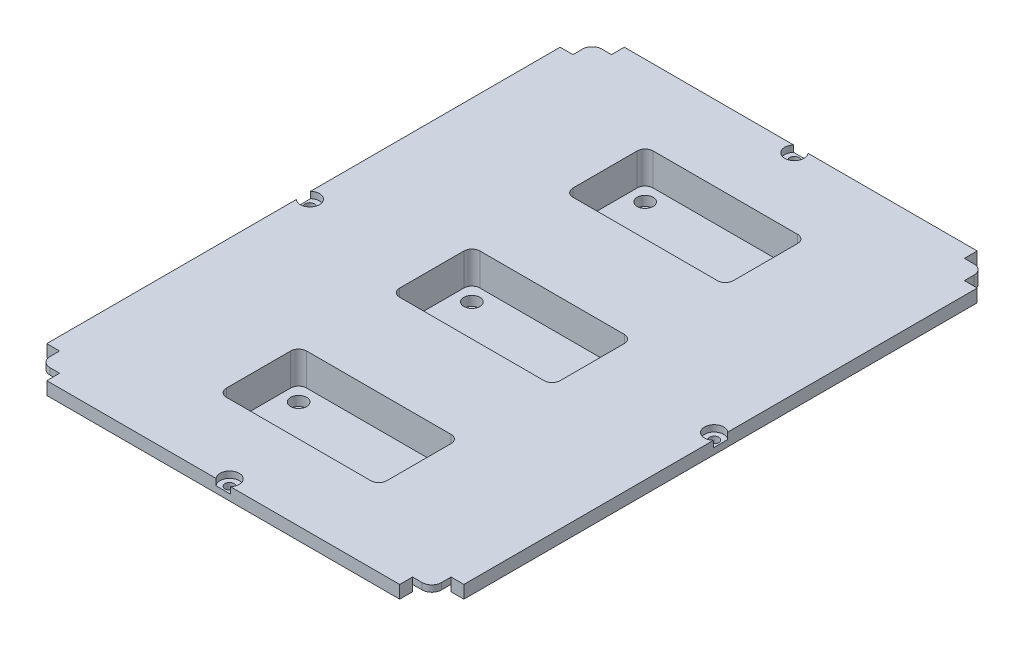
SolidWorks part; units mm, degrees
ref_plane "Спереди" through (0, 0, 0) normal (0, 0, 1) x (1, 0, 0)
ref_plane "Сверху" through (0, 0, 0) normal (0, 1, 0) x (1, 0, 0)
ref_plane "Справа" through (0, 0, 0) normal (1, 0, 0) x (0, 0, -1)
sketch "Эскиз1" plane through (0, 0, 0) normal (0, 1, 0) x (1, 0, 0)
  line L1 (-65, -90) -> (65, -90)
  line L2 (-65, -90) -> (-65, 90)
  line L3 (-65, 90) -> (65, 90)
  line L4 (65, -90) -> (65, 90)
  line L5 (-65, -90) -> (65, 90) construction
  line L6 (-65, 90) -> (65, -90) construction
  point P0 (0, 0)
  dimension "D1" = 130
  dimension "D2" = 180
extrude "Бобышка-Вытянуть1" add sketch "Эскиз1" along normal blind 55
sketch "Эскиз2" plane through (0, 0, 90) normal (0, 0, 1) x (1, 0, 0)
  line L0 (-1050, 27.5) -> (48950, 27.5) construction
  line L1 (-65, 55) -> (-65, 0) construction
  line L2 (0, -999.2777) -> (0, 49000.7223) construction
  line L4 (-22.5, 15) -> (22.5, 15)
  line L5 (-25, 17.5) -> (-25, 37.5)
  line L6 (-22.5, 40) -> (22.5, 40)
  line L7 (25, 17.5) -> (25, 37.5)
  line L8 (-25, 15) -> (25, 40) construction
  line L9 (-25, 40) -> (25, 15) construction
  arc A0 (-22.5, 40) -> (-25, 37.5) centre (-22.5, 37.5) ccw
  arc A1 (-25, 17.5) -> (-22.5, 15) centre (-22.5, 17.5) ccw
  arc A2 (25, 17.5) -> (22.5, 15) centre (22.5, 17.5) cw
  arc A3 (25, 37.5) -> (22.5, 40) centre (22.5, 37.5) ccw
  point P5 (-65, 27.5)
  point P6 (0, 27.5)
  dimension "D3" = 2.5
  dimension "D4" = 2.5
  dimension "D1" = 25
  dimension "D2" = 50
extrude "Вырез-Вытянуть1" cut sketch "Эскиз2" against normal blind 10
sketch "Эскиз4" plane through (0, 55, 0) normal (0, 1, 0) x (1, 0, 0)
  line L0 (0, -1000) -> (0, 49000) construction
  line L1 (-1000, 0) -> (49000, 0) construction
  line L2 (-22.5, 41.5) -> (22.5, 41.5)
  line L3 (-25, 44) -> (-25, 64)
  line L4 (-22.5, 66.5) -> (22.5, 66.5)
  line L5 (-22.5, -12.5) -> (22.5, -12.5)
  line L6 (-25, -10) -> (-25, 10)
  line L7 (-22.5, 12.5) -> (22.5, 12.5)
  line L8 (25, -10) -> (25, 10)
  line L9 (-25, -12.5) -> (25, 12.5) construction
  line L10 (-25, 12.5) -> (25, -12.5) construction
  line L11 (25, 44) -> (25, 64)
  line L12 (-25, 41.5) -> (25, 66.5) construction
  line L13 (-25, 66.5) -> (25, 41.5) construction
  line L14 (-25, -12.5) -> (25, -12.5) [skipped]
  line L15 (-25, -12.5) -> (-25, 12.5) [skipped]
  line L16 (-25, 12.5) -> (25, 12.5) [skipped]
  line L17 (25, -12.5) -> (25, 12.5) [skipped]
  line L18 (-25, -12.5) -> (25, 12.5) construction
  line L19 (-25, 12.5) -> (25, -12.5) construction
  line L20 (-22.5, -66.5) -> (22.5, -66.5)
  line L21 (-25, -64) -> (-25, -44)
  line L22 (-22.5, -41.5) -> (22.5, -41.5)
  line L23 (25, -64) -> (25, -44)
  line L24 (-25, -66.5) -> (25, -41.5) construction
  line L25 (-25, -41.5) -> (25, -66.5) construction
  arc A0 (22.5, -41.5) -> (25, -44) centre (22.5, -44) cw
  arc A1 (25, -64) -> (22.5, -66.5) centre (22.5, -64) cw
  arc A2 (-22.5, -66.5) -> (-25, -64) centre (-22.5, -64) cw
  arc A3 (-25, -44) -> (-22.5, -41.5) centre (-22.5, -44) cw
  arc A4 (-25, 64) -> (-22.5, 66.5) centre (-22.5, 64) cw
  arc A5 (-22.5, 12.5) -> (-25, 10) centre (-22.5, 10) ccw
  arc A6 (25, -10) -> (22.5, -12.5) centre (22.5, -10) cw
  arc A7 (22.5, 66.5) -> (25, 64) centre (22.5, 64) cw
  arc A8 (25, 44) -> (22.5, 41.5) centre (22.5, 44) cw
  arc A9 (-22.5, 41.5) -> (-25, 44) centre (-22.5, 44) cw
  arc A10 (22.5, 12.5) -> (25, 10) centre (22.5, 10) cw
  arc A11 (-22.5, -12.5) -> (-25, -10) centre (-22.5, -10) cw
  point P8 (0, 0)
  point P9 (0, 54)
  point P18 (0, 0)
  point P23 (0, -54)
  dimension "D7" = 2.5
  dimension "D8" = 2.5
  dimension "D1" = 25
  dimension "D2" = 50
  dimension "D5" = 41.5
  dimension "D6" = 41.5
  dimension "D3" = 2
  dimension "D4" = 2
extrude "Вырез-Вытянуть2" cut sketch "Эскиз4" against normal blind 10
mirror "Зеркальное отражение1" about plane through (0, 0, 0) normal (0, 0, 1) of "Вырез-Вытянуть1"
shell "Оболочка1" thickness 4
sketch "Эскиз5" plane through (-65, 0, 0) normal (-1, 0, 0) x (0, 0, 1)
  line L0 (45, 28.75) -> (45, 11.25) construction
  line L2 (90, 55) -> (90, 0) construction
  line L4 (-90, 0) -> (90, 0) construction
  line L7 (-1075, 20) -> (48925, 20) construction
  line L8 (-90, 55) -> (-90, 0) construction
  circle A3 centre (45, 28.75) radius 1.45
  circle A4 centre (45, 11.25) radius 1.45
  circle A5 centre (65.6, 20) radius 4
  circle A6 centre (-65.6, 20) radius 5
  dimension "D2" = 17.5
  dimension "D3" = 20
  dimension "D6" = 10
  dimension "D1" = 17.5
  dimension "D5" = 2.9
  dimension "D9" = 45
  dimension "D10" = 20.6
  dimension "D11" = 8
  dimension "D4" = 24.4
extrude "Вырез-Вытянуть3" cut sketch "Эскиз5" against normal blind 15
sketch "Эскиз6" plane through (-65, 0, 0) normal (-1, 0, 0) x (0, 0, 1)
  circle A2 centre (45, 28.75) radius 3
  circle A3 centre (45, 11.25) radius 3
  dimension "D1" = 6
extrude "Вырез-Вытянуть4" cut sketch "Эскиз6" against normal blind 2.5
sketch "Эскиз11" plane through (-61, 0, 0) normal (1, 0, 0) x (0, 0, -1)
  circle A1 centre (-65.6, 20) radius 5
  dimension "D1" = 10
extrude "Вырез-Вытянуть16" cut sketch "Эскиз11" against normal blind 1
mirror "Зеркальное отражение2" about plane through (0, 0, 0) normal (1, 0, 0) of "Вырез-Вытянуть3", "Вырез-Вытянуть4", "Вырез-Вытянуть16"
sketch "Эскиз12" plane through (0, 11, 0) normal (0, -1, 0) x (-1, 0, 0)
  line L0 (-1014.7864, -78) -> (48985.2136, -78) construction
  line L1 (22.5, -76) -> (-22.5, -76) construction
  line L2 (0, -1061) -> (0, 48939) construction
  line L3 (-10, -1061) -> (-10, 48939) construction
  line L4 (10, -1061) -> (10, 48939) construction
  circle A0 centre (-10, -78) radius 1.45
  circle A1 centre (10, -78) radius 1.45
  point P7 (0, -76)
  dimension "D4" = 2.9
  dimension "D1" = 2
  dimension "D2" = 20
  dimension "D3" = 10
extrude "Вырез-Вытянуть17" cut sketch "Эскиз12" against normal blind 14
sketch "Эскиз15" plane through (0, 45, 0) normal (0, 1, 0) x (1, 0, 0)
  line L0 (-1010.1672, -62.5) -> (48989.8328, -62.5) construction
  line L1 (0, -1031.5) -> (0, 48968.5) construction
  line L2 (-7.6, -63.8) -> (7.6, -63.8)
  line L3 (-7.6, -63.8) -> (-7.6, -61.2)
  line L4 (-7.6, -61.2) -> (7.6, -61.2)
  line L5 (7.6, -63.8) -> (7.6, -61.2)
  line L6 (-7.6, -63.8) -> (7.6, -61.2) construction
  line L7 (-7.6, -61.2) -> (7.6, -63.8) construction
  line L8 (22.5, -41.5) -> (-22.5, -41.5) construction
  line L9 (-22.5, -66.5) -> (22.5, -66.5) construction
  line L10 (-7.6, -9.8) -> (7.6, -9.8)
  line L11 (-7.6, -9.8) -> (-7.6, -7.2)
  line L12 (-7.6, -7.2) -> (7.6, -7.2)
  line L13 (7.6, -9.8) -> (7.6, -7.2)
  line L14 (-7.6, -9.8) -> (7.6, -7.2) construction
  line L15 (-7.6, -7.2) -> (7.6, -9.8) construction
  line L16 (-7.6, 44.2) -> (7.6, 44.2)
  line L17 (-7.6, 44.2) -> (-7.6, 46.8)
  line L18 (-7.6, 46.8) -> (7.6, 46.8)
  line L19 (7.6, 44.2) -> (7.6, 46.8)
  line L20 (-7.6, 44.2) -> (7.6, 46.8) construction
  line L21 (-7.6, 46.8) -> (7.6, 44.2) construction
  line L23 (22.5, 12.5) -> (-22.5, 12.5) construction
  line L24 (-7.6, -59.8) -> (7.6, -59.8)
  line L25 (-7.6, -59.8) -> (-7.6, -57.2)
  line L26 (-7.6, -57.2) -> (7.6, -57.2)
  line L27 (7.6, -59.8) -> (7.6, -57.2)
  line L28 (-7.6, -59.8) -> (7.6, -57.2) construction
  line L29 (-7.6, -57.2) -> (7.6, -59.8) construction
  line L30 (-7.6, -5.8) -> (7.6, -5.8)
  line L31 (-7.6, -5.8) -> (-7.6, -3.2)
  line L32 (-7.6, -3.2) -> (7.6, -3.2)
  line L33 (7.6, -5.8) -> (7.6, -3.2)
  line L34 (-7.6, -5.8) -> (7.6, -3.2) construction
  line L35 (-7.6, -3.2) -> (7.6, -5.8) construction
  line L36 (-7.6, 48.2) -> (7.6, 48.2)
  line L37 (-7.6, 48.2) -> (-7.6, 50.8)
  line L38 (-7.6, 50.8) -> (7.6, 50.8)
  line L39 (7.6, 48.2) -> (7.6, 50.8)
  line L40 (-7.6, 48.2) -> (7.6, 50.8) construction
  line L41 (-7.6, 50.8) -> (7.6, 48.2) construction
  line L42 (-22.5, -12.5) -> (22.5, -12.5) construction
  circle A0 centre (-20, -46.5) radius 2.5
  circle A1 centre (20, -46.5) radius 2.5
  circle A2 centre (-20, 7.5) radius 2.5
  circle A3 centre (20, 7.5) radius 2.5
  circle A4 centre (-20, 61.5) radius 2.5
  circle A5 centre (20, 61.5) radius 2.5
  point P1 (0, -62.5)
  point P12 (0, -41.5)
  point P16 (0, -8.5)
  point P21 (0, 45.5)
  point P41 (0, -4.5)
  point P42 (0, -58.5)
  point P51 (0, 49.5)
  dimension "D6" = 40
  dimension "D8" = 5
  dimension "D1" = 2.6
  dimension "D2" = 15.2
  dimension "D3" = 4
  dimension "D4" = 3
  dimension "D5" = 4
  dimension "D7" = 40
  dimension "D9" = 5
  dimension "D10" = 3
  dimension "D11" = 5
  dimension "D13" = 4
  dimension "D15" = 4
  dimension "D12" = 2
  dimension "D14" = 3
extrude "Вырез-Вытянуть20" cut sketch "Эскиз15" against normal blind 3
sketch "Эскиз16" plane through (0, 42, 0) normal (0, 1, 0) x (1, 0, 0)
  line L0 (-7.6, -62.5) -> (7.6, -62.5) construction
  line L1 (-7.6, -61.2) -> (-7.6, -63.8) construction
  line L2 (7.6, -63.8) -> (7.6, -61.2) construction
  line L3 (0, -1000) -> (0, 49000) construction
  line L4 (-7, -63.4) -> (7, -63.4)
  line L5 (-7, -63.4) -> (-7, -61.6)
  line L6 (-7, -61.6) -> (7, -61.6)
  line L7 (7, -63.4) -> (7, -61.6)
  line L8 (-7, -63.4) -> (7, -61.6) construction
  line L9 (-7, -61.6) -> (7, -63.4) construction
  line L10 (-7, -9.4) -> (7, -9.4)
  line L11 (-7, -9.4) -> (-7, -7.6)
  line L12 (-7, -7.6) -> (7, -7.6)
  line L13 (7, -9.4) -> (7, -7.6)
  line L14 (-7.6, -8.5) -> (7.6, -8.5) construction
  line L15 (-7, -9.4) -> (7, -7.6) construction
  line L16 (-7, -7.6) -> (7, -9.4) construction
  line L17 (-7, 44.6) -> (7, 44.6)
  line L18 (-7, 44.6) -> (-7, 46.4)
  line L19 (-7, 46.4) -> (7, 46.4)
  line L20 (7, 44.6) -> (7, 46.4)
  line L21 (-7.6, 45.5) -> (7.6, 45.5) construction
  line L22 (-7, 44.6) -> (7, 46.4) construction
  line L23 (-7, 46.4) -> (7, 44.6) construction
  line L24 (-7.6, -7.2) -> (-7.6, -9.8) construction
  line L25 (-7.6, -58.5) -> (7.6, -58.5) construction
  line L26 (-7, -59.4) -> (7, -59.4)
  line L27 (-7, -59.4) -> (-7, -57.6)
  line L28 (-7, -57.6) -> (7, -57.6)
  line L29 (7, -59.4) -> (7, -57.6)
  line L30 (-7, -59.4) -> (7, -57.6) construction
  line L31 (-7, -57.6) -> (7, -59.4) construction
  line L32 (-7.6, -57.2) -> (-7.6, -59.8) construction
  line L33 (7.6, -59.8) -> (7.6, -57.2) construction
  line L34 (-7.6, -4.5) -> (7.6, -4.5) construction
  line L35 (-7.6, -3.2) -> (-7.6, -5.8) construction
  line L36 (7.6, -5.8) -> (7.6, -3.2) construction
  line L37 (-7.6, -9.8) -> (7.6, -9.8) construction
  line L38 (-7, -5.4) -> (7, -5.4)
  line L39 (-7, -5.4) -> (-7, -3.6)
  line L40 (-7, -3.6) -> (7, -3.6)
  line L41 (7, -5.4) -> (7, -3.6)
  line L42 (-7, -5.4) -> (7, -3.6) construction
  line L43 (-7, -3.6) -> (7, -5.4) construction
  line L44 (7.6, -9.8) -> (7.6, -7.2) construction
  line L45 (-7.6, 46.8) -> (-7.6, 44.2) construction
  line L46 (7.6, 44.2) -> (7.6, 46.8) construction
  line L47 (-7.6, 44.2) -> (7.6, 44.2) construction
  line L48 (-7.6, 49.5) -> (7.6, 49.5) construction
  line L49 (-7.6, 50.8) -> (-7.6, 48.2) construction
  line L50 (7.6, 48.2) -> (7.6, 50.8) construction
  line L52 (-7, 48.6) -> (7, 48.6)
  line L53 (-7, 48.6) -> (-7, 50.4)
  line L54 (-7, 50.4) -> (7, 50.4)
  line L55 (7, 48.6) -> (7, 50.4)
  line L56 (-7, 48.6) -> (7, 50.4) construction
  line L57 (-7, 50.4) -> (7, 48.6) construction
  point P6 (0, -62.5)
  point P12 (0, -58.5)
  point P17 (0, -8.5)
  point P24 (0, 36.6)
  point P41 (0, -4.5)
  point P54 (0, 49.5)
  dimension "D1" = 1.8
  dimension "D2" = 14
  dimension "D4" = 0.4
  dimension "D3" = 0.4
extrude "Вырез-Вытянуть21" cut sketch "Эскиз16" against normal blind 3
sketch "Эскиз17" plane through (0, 0, 80) normal (0, 0, 1) x (1, 0, 0)
  line L0 (-7.6, 17.5) -> (7.6, 17.5)
  line L1 (-7.6, 17.5) -> (-7.6, 20.1)
  line L2 (-7.6, 20.1) -> (7.6, 20.1)
  line L3 (7.6, 17.5) -> (7.6, 20.1)
  line L4 (-7.6, 17.5) -> (7.6, 20.1) construction
  line L5 (-7.6, 20.1) -> (7.6, 17.5) construction
  line L7 (-7.6, 21.5) -> (7.6, 21.5)
  line L8 (-22.5, 15) -> (22.5, 15) construction
  line L9 (0, -965) -> (0, 49035) construction
  line L10 (22.5, 40) -> (-22.5, 40) construction
  line L11 (-7.6, 21.5) -> (-7.6, 24.1)
  line L12 (-7.6, 24.1) -> (7.6, 24.1)
  line L13 (7.6, 21.5) -> (7.6, 24.1)
  line L14 (-7.6, 21.5) -> (7.6, 24.1) construction
  line L15 (-7.6, 24.1) -> (7.6, 21.5) construction
  circle A0 centre (-20, 35) radius 2.5
  circle A1 centre (20, 35) radius 2.5
  point P0 (0, 18.8)
  point P11 (0, 22.8)
  point P20 (0, 40)
  dimension "D5" = 5
  dimension "D8" = 4
  dimension "D1" = 2.6
  dimension "D2" = 15.2
  dimension "D3" = 40
  dimension "D4" = 40
  dimension "D6" = 2.5
  dimension "D7" = 5
extrude "Вырез-Вытянуть22" cut sketch "Эскиз17" against normal blind 3
sketch "Эскиз18" plane through (0, 0, 77) normal (0, 0, 1) x (1, 0, 0)
  line L0 (-7.6, 18.8) -> (7.6, 18.8) construction
  line L1 (-7.6, 20.1) -> (-7.6, 17.5) construction
  line L2 (7.6, 17.5) -> (7.6, 20.1) construction
  line L3 (0, -980.9) -> (0, 49019.1) construction
  line L4 (-7, 17.9) -> (7, 17.9)
  line L5 (-7, 17.9) -> (-7, 19.7)
  line L6 (-7, 19.7) -> (7, 19.7)
  line L7 (7, 17.9) -> (7, 19.7)
  line L8 (-7, 17.9) -> (7, 19.7) construction
  line L9 (-7, 19.7) -> (7, 17.9) construction
  line L10 (7.6, 24.1) -> (-7.6, 24.1) construction
  line L12 (-7, 21.9) -> (7, 21.9)
  line L13 (-7, 21.9) -> (-7, 23.7)
  line L14 (-7, 23.7) -> (7, 23.7)
  line L15 (7, 21.9) -> (7, 23.7)
  line L16 (-7, 21.9) -> (7, 23.7) construction
  line L17 (-7, 23.7) -> (7, 21.9) construction
  point P6 (0, 18.8)
  point P12 (0, 22.8)
  point P16 (0, 24.1)
  dimension "D1" = 1.8
  dimension "D2" = 14
  dimension "D3" = 4
extrude "Вырез-Вытянуть23" cut sketch "Эскиз18" against normal blind 3
sketch "Эскиз19" plane through (0, 0, -80) normal (0, 0, -1) x (1, 0, 0)
  line L0 (-7.6, -37.5) -> (7.6, -37.5)
  line L1 (-7.6, -37.5) -> (-7.6, -34.9)
  line L2 (-7.6, -34.9) -> (7.6, -34.9)
  line L3 (7.6, -37.5) -> (7.6, -34.9)
  line L4 (-7.6, -37.5) -> (7.6, -34.9) construction
  line L5 (-7.6, -34.9) -> (7.6, -37.5) construction
  line L6 (0, -1010) -> (0, 48990) construction
  line L7 (-22.5, -15) -> (22.5, -15) construction
  line L9 (-7.6, -33.5) -> (7.6, -33.5)
  line L10 (22.5, -40) -> (-22.5, -40) construction
  line L11 (-7.6, -33.5) -> (-7.6, -30.9)
  line L12 (-7.6, -30.9) -> (7.6, -30.9)
  line L13 (7.6, -33.5) -> (7.6, -30.9)
  line L14 (-7.6, -33.5) -> (7.6, -30.9) construction
  line L15 (-7.6, -30.9) -> (7.6, -33.5) construction
  circle A0 centre (-20, -20) radius 2.5
  circle A1 centre (20, -20) radius 2.5
  point P0 (0, -36.2)
  point P14 (0, -15)
  point P16 (0, -32.2)
  dimension "D5" = 5
  dimension "D7" = 2.5
  dimension "D1" = 2.6
  dimension "D2" = 15.2
  dimension "D3" = 40
  dimension "D4" = 40
  dimension "D6" = 5
  dimension "D8" = 4
extrude "Вырез-Вытянуть24" cut sketch "Эскиз19" against normal blind 3
sketch "Эскиз20" plane through (0, 0, -77) normal (0, 0, -1) x (1, 0, 0)
  line L0 (-1007.6, -36.2) -> (48992.4, -36.2) construction
  line L1 (-7.6, -34.9) -> (-7.6, -37.5) construction
  line L3 (-7, -37.1) -> (7, -37.1)
  line L4 (-7, -37.1) -> (-7, -35.3)
  line L5 (-7, -35.3) -> (7, -35.3)
  line L6 (7, -37.1) -> (7, -35.3)
  line L7 (-7, -37.1) -> (7, -35.3) construction
  line L8 (-7, -35.3) -> (7, -37.1) construction
  line L9 (-7, -31.3) -> (7, -31.3)
  line L10 (0, -1029.9) -> (0, 48970.1) construction
  line L11 (7.6, -34.9) -> (-7.6, -34.9) construction
  line L12 (-7, -31.3) -> (-7, -33.1)
  line L13 (-7, -33.1) -> (7, -33.1)
  line L14 (7, -31.3) -> (7, -33.1)
  line L15 (-7, -31.3) -> (7, -33.1) construction
  line L16 (-7, -33.1) -> (7, -31.3) construction
  point P1 (0, -36.2)
  point P5 (-7.6, -36.2)
  point P10 (0, -32.2)
  point P18 (0, -34.9)
  dimension "D1" = 1.8
  dimension "D2" = 14
  dimension "D3" = 4
extrude "Вырез-Вытянуть25" cut sketch "Эскиз20" against normal blind 5
sketch "Эскиз21" plane through (0, 0, 90) normal (0, 0, -1) x (1, 0, 0)
  line L0 (-975, -27.5) -> (49025, -27.5) construction
  line L1 (35.25, -34.75) -> (44.75, -34.75)
  line L2 (35.25, -34.75) -> (35.25, -20.25)
  line L3 (35.25, -20.25) -> (44.75, -20.25)
  line L4 (44.75, -34.75) -> (44.75, -20.25)
  line L5 (35.25, -34.75) -> (44.75, -20.25) construction
  line L6 (35.25, -20.25) -> (44.75, -34.75) construction
  line L7 (25, -17.5) -> (25, -37.5) construction
  line L8 (40, -1022.5) -> (40, 48977.5) construction
  line L9 (65, -55) -> (65, 0) construction
  point P0 (40, -27.5)
  point P10 (25, -27.5)
  dimension "D1" = 9.5
  dimension "D2" = 14.5
  dimension "D3" = 25
extrude "Вырез-Вытянуть26" cut sketch "Эскиз21" along normal blind 4
sketch "Эскиз22" plane through (0, 0, 0) normal (0, -1, 0) x (-1, 0, 0)
  line L0 (-63, -925) -> (-63, 49075) construction
  line L2 (-65, -90) -> (-65, 90) construction
  line L3 (-1046.2998, 88) -> (48953.7002, 88) construction
  line L4 (-65, 90) -> (65, 90) construction
  line L5 (63, -925) -> (63, 49075) construction
  line L6 (65, 90) -> (65, -90) construction
  line L7 (-1052.5, -88) -> (48947.5, -88) construction
  line L8 (65, -90) -> (-65, -90) construction
  line L9 (0, -925) -> (0, 49075) construction
  line L10 (-1052.5, 0) -> (48947.5, 0) construction
  circle A4 centre (0, 88) radius 1.425
  circle A5 centre (0, -88) radius 1.425
  circle A6 centre (-63, 0) radius 1.425
  circle A7 centre (63, 0) radius 1.425
  point P27 (0, 90)
  point P34 (-65, 0)
  dimension "D5" = 2.85
  dimension "D1" = 2
  dimension "D2" = 2
  dimension "D3" = 2
  dimension "D4" = 2
extrude "Вырез-Вытянуть27" cut sketch "Эскиз22" against normal blind 9
sketch "Эскиз24" plane through (-65, 0, 0) normal (-1, 0, 0) x (0, 0, 1)
  line L0 (0, -1000) -> (0, 49000) construction
  line L1 (16, -988.2808) -> (16, 49011.7192) construction
  line L2 (-90, 0) -> (90, 0) construction
  circle A0 centre (16, 16) radius 1.475
  circle A1 centre (16, 27.5) radius 1.475
  dimension "D4" = 2.95
  dimension "D1" = 11.5
  dimension "D2" = 16
  dimension "D3" = 16
extrude "Вырез-Вытянуть28" cut sketch "Эскиз24" against normal through all
fillet "Скругление1" radius 10 4 edges at (65, 27.5, -90) (-65, 27.5, -90) (65, 27.5, 90) (-65, 27.5, 90)
sketch "Эскиз26" plane through (61, 0, 0) normal (-1, 0, 0) x (0, 0, 1)
  line L1 (17.6454, 18.85) -> (14.3546, 18.85)
  line L2 (14.3546, 18.85) -> (12.7091, 16)
  line L3 (12.7091, 16) -> (14.3546, 13.15)
  line L4 (14.3546, 13.15) -> (17.6454, 13.15)
  line L5 (17.6454, 13.15) -> (19.2909, 16)
  line L6 (19.2909, 16) -> (17.6454, 18.85)
  line L7 (17.6454, 30.35) -> (14.3546, 30.35)
  line L8 (14.3546, 30.35) -> (12.7091, 27.5)
  line L9 (12.7091, 27.5) -> (14.3546, 24.65)
  line L10 (14.3546, 24.65) -> (17.6454, 24.65)
  line L11 (17.6454, 24.65) -> (19.2909, 27.5)
  line L12 (19.2909, 27.5) -> (17.6454, 30.35)
  circle A0 centre (16, 16) radius 2.85 construction
  circle A1 centre (16, 27.5) radius 2.85 construction
  dimension "D1" = 5.7
extrude "Вырез-Вытянуть29" cut sketch "Эскиз26" against normal blind 2 and the other way blind 124
fillet "Скругление2" radius 3 4 edges at (61, 25.5, 86) (61, 25.5, -86) (-61, 25.5, -86) (-61, 25.5, 86)
sketch "Эскиз27" plane through (0, 0, 0) normal (0, -1, 0) x (1, 0, 0)
  line L0 (-55, -90) -> (-45, -90)
  line L1 (55, -90) -> (-55, -90) construction
  line L2 (-45, -90) -> (-45, -86)
  line L3 (58, -86) -> (-58, -86) construction
  line L4 (-45, -86) -> (-58, -86)
  line L6 (-61, -83) -> (-61, -70)
  line L7 (-61, -83) -> (-61, 83) construction
  line L8 (-61, -70) -> (-65, -70)
  line L9 (-65, -80) -> (-65, 80) construction
  line L10 (-65, -70) -> (-65, -80)
  line L11 (0, -1000) -> (0, 49000) construction
  line L12 (-1000, 0) -> (49000, 0) construction
  line L13 (65, -70) -> (65, -80)
  line L14 (61, -70) -> (65, -70)
  line L15 (61, -83) -> (61, -70)
  line L16 (45, -86) -> (58, -86)
  line L17 (45, -90) -> (45, -86)
  line L18 (55, -90) -> (45, -90)
  line L19 (55, 90) -> (45, 90)
  line L20 (45, 90) -> (45, 86)
  line L21 (45, 86) -> (58, 86)
  line L22 (61, 83) -> (61, 70)
  line L23 (61, 70) -> (65, 70)
  line L24 (65, 70) -> (65, 80)
  line L25 (-65, 70) -> (-65, 80)
  line L26 (-61, 70) -> (-65, 70)
  line L27 (-61, 83) -> (-61, 70)
  line L28 (-45, 86) -> (-58, 86)
  line L29 (-45, 90) -> (-45, 86)
  line L30 (-55, 90) -> (-45, 90)
  arc A1 (-65, -80) -> (-55, -90) centre (-55, -80) ccw construction
  arc A4 (61, -83) -> (58, -86) centre (58, -83) cw
  arc A5 (-65, -80) -> (-55, -90) centre (-55, -80) ccw
  arc A6 (65, -80) -> (55, -90) centre (55, -80) cw
  arc A7 (-61, 83) -> (-58, 86) centre (-58, 83) cw
  arc A8 (-61, -83) -> (-58, -86) centre (-58, -83) ccw construction
  arc A9 (-61, -83) -> (-58, -86) centre (-58, -83) ccw
  arc A10 (65, 80) -> (55, 90) centre (55, 80) ccw
  arc A11 (-65, 80) -> (-55, 90) centre (-55, 80) cw
  arc A12 (61, 83) -> (58, 86) centre (58, 83) ccw
  dimension "D1" = 10
extrude "Бобышка-Вытянуть2" add sketch "Эскиз27" along normal blind 3
sketch "Эскиз28" plane through (0, 0, 0) normal (0, -1, 0) x (1, 0, 0)
  line L0 (-61, 70) -> (-61, 83) construction
  line L2 (-61, 70) -> (-61, 83)
  line L3 (-58, 86) -> (-45, 86)
  line L4 (-45, 86) -> (-45, 86.5)
  line L5 (-45, 86) -> (-45, 90) construction
  line L6 (-45, 86.5) -> (-58, 86.5)
  line L7 (-1000, 0) -> (49000, 0) construction
  line L8 (-61.5, 83) -> (-61.5, 70)
  line L9 (-65, 70) -> (-61, 70) construction
  line L10 (-61.5, 70) -> (-61, 70)
  line L11 (0, -1000) -> (0, 49000) construction
  line L12 (61.5, 70) -> (61, 70)
  line L13 (61.5, 83) -> (61.5, 70)
  line L14 (45, 86.5) -> (58, 86.5)
  line L15 (45, 86) -> (45, 86.5)
  line L16 (58, 86) -> (45, 86)
  line L17 (61, 70) -> (61, 83)
  line L18 (61, -70) -> (61, -83)
  line L19 (58, -86) -> (45, -86)
  line L20 (45, -86) -> (45, -86.5)
  line L21 (45, -86.5) -> (58, -86.5)
  line L22 (61.5, -83) -> (61.5, -70)
  line L23 (61.5, -70) -> (61, -70)
  line L24 (-61.5, -70) -> (-61, -70)
  line L25 (-61.5, -83) -> (-61.5, -70)
  line L26 (-45, -86.5) -> (-58, -86.5)
  line L27 (-45, -86) -> (-45, -86.5)
  line L28 (-58, -86) -> (-45, -86)
  line L29 (-61, -70) -> (-61, -83)
  arc A0 (-58, 86) -> (-61, 83) centre (-58, 83) ccw construction
  arc A1 (-58, 86) -> (-61, 83) centre (-58, 83) ccw
  arc A2 (-61.5, 83) -> (-58, 86.5) centre (-58, 83) cw
  arc A3 (61.5, 83) -> (58, 86.5) centre (58, 83) ccw
  arc A4 (58, 86) -> (61, 83) centre (58, 83) cw
  arc A5 (58, -86) -> (61, -83) centre (58, -83) ccw
  arc A6 (61.5, -83) -> (58, -86.5) centre (58, -83) cw
  arc A7 (-61.5, -83) -> (-58, -86.5) centre (-58, -83) ccw
  arc A8 (-58, -86) -> (-61, -83) centre (-58, -83) cw
  dimension "D1" = 0.5
extrude "Вырез-Вытянуть30" cut sketch "Эскиз28" along normal blind 2.5
sketch "Эскиз30" plane through (0, 51, 0) normal (0, -1, 0) x (1, 0, 0)
  line L0 (-29, -10) -> (-29, 10) construction
  line L1 (-58.5, 86) -> (-29, 86)
  line L2 (-61, 83.5) -> (-61, 6)
  line L3 (-61, 6) -> (-29, 6)
  line L4 (-29, 86) -> (-29, 6)
  line L5 (-58, 86) -> (58, 86) construction
  line L6 (-61, -83) -> (-61, 83) construction
  line L7 (0, -1000) -> (0, 49000) construction
  line L8 (29, 86) -> (29, 6)
  line L9 (61, 6) -> (29, 6)
  line L10 (61, 83.5) -> (61, 6)
  line L11 (58.5, 86) -> (29, 86)
  arc A0 (-58.5, 86) -> (-61, 83.5) centre (-58.5, 83.5) ccw
  arc A1 (58.5, 86) -> (61, 83.5) centre (58.5, 83.5) cw
  dimension "D1" = 2.5
  dimension "D2" = 80
extrude "Вырез-Вытянуть32" cut sketch "Эскиз30" against normal blind 2
sketch "Эскиз29" plane through (-61, 0, 0) normal (1, 0, 0) x (0, 0, -1)
  line L1 (83, 51) -> (-6, 51) construction
  line L2 (-86, 0) -> (-86, 51) construction
  line L3 (0, -1000) -> (0, 49000) construction
  line L4 (90, 55) -> (90, -3) construction
  line L6 (-80, 55) -> (80, 55) construction
  circle A0 centre (-73.5, 43) radius 1.45
  circle A1 centre (-18.5, 43) radius 1.45
  circle A4 centre (18.5, 41) radius 1.45
  circle A5 centre (73.5, 41) radius 1.45
  dimension "D1" = 8
  dimension "D4" = 2.9
  dimension "D5" = 55
  dimension "D2" = 12.5
  dimension "D3" = 55
  dimension "D6" = 16.5
  dimension "D7" = 14
extrude "Вырез-Вытянуть31" cut sketch "Эскиз29" against normal through all both and the other way through all
sketch "Эскиз31" plane through (0, 41, 0) normal (0, -1, 0) x (1, 0, 0)
  line L0 (26, -1043.9084) -> (26, 48956.0916) construction
  line L2 (29, 64) -> (29, 44) construction
  line L3 (29, -76) -> (29, -86) construction
  line L4 (26, 81) -> (29, 81)
  line L5 (26, 81) -> (26, -81)
  line L6 (26, -81) -> (29, -81)
  line L7 (29, 81) -> (29, -81)
  line L8 (22.5, 76) -> (22.5, 86) construction
  line L9 (-977.5, 81) -> (49022.5, 81) construction
  line L10 (0, -1000) -> (0, 49000) construction
  line L11 (-26, -1043.9084) -> (-26, 48956.0916) construction
  line L12 (-29, 81) -> (-29, -81)
  line L13 (-26, -81) -> (-29, -81)
  line L14 (-26, 81) -> (-26, -81)
  line L15 (-26, 81) -> (-29, 81)
  point P16 (22.5, 81)
  dimension "D1" = 3
extrude "Вырез-Вытянуть33" cut sketch "Эскиз31" against normal up to surface and the other way blind 20 up to face at (0, 51, 27)
sketch "Эскиз32" plane through (61, 0, 0) normal (-1, 0, 0) x (0, 0, 1)
  line L0 (-83, 51) -> (-83, 0) construction
  line L1 (-83, 7) -> (-81.5, 7)
  line L2 (-83, 7) -> (-83, 24.5)
  line L3 (-83, 24.5) -> (-81.5, 24.5)
  line L4 (-81.5, 7) -> (-81.5, 24.5)
  line L5 (83, 0) -> (-83, 0) construction
  dimension "D1" = 17.5
  dimension "D2" = 1.5
  dimension "D3" = 7
extrude "Вырез-Вытянуть34" cut sketch "Эскиз32" against normal blind 3 contours L1 L4 L3 L2
sketch "Эскиз33" plane through (61, 0, 0) normal (-1, 0, 0) x (0, 0, 1)
  line L0 (-81.5, 7) -> (-81.5, 24.5) construction
  line L1 (-82.5, 20.75) -> (-78.5, 20.75)
  line L2 (-82.5, 20.75) -> (-82.5, 10.75)
  line L3 (-82.5, 10.75) -> (-78.5, 10.75)
  line L4 (-78.5, 20.75) -> (-78.5, 10.75)
  line L5 (-1081.5, 15.75) -> (48918.5, 15.75) construction
  point P7 (-78.5, 15.75)
  point P9 (-81.5, 15.75)
  dimension "D1" = 10
  dimension "D2" = 4
  dimension "D3" = 3
extrude "Вырез-Вытянуть35" cut sketch "Эскиз33" against normal blind 4
sketch "Эскиз34" plane through (0, 0, -86) normal (0, 0, 1) x (1, 0, 0)
  line L0 (61, 51) -> (61, 24.5) construction
  line L1 (34, 7) -> (61, 7)
  line L2 (34, 7) -> (34, 24.5)
  line L3 (34, 24.5) -> (61, 24.5)
  line L4 (61, 7) -> (61, 24.5)
  line L5 (58, 0) -> (-58, 0) construction
  dimension "D1" = 7
  dimension "D2" = 27
  dimension "D3" = 17.5
extrude "Бобышка-Вытянуть3" add sketch "Эскиз34" along normal blind 3
sketch "Эскиз35" plane through (61, 0, 0) normal (-1, 0, 0) x (0, 0, 1)
  line L0 (-90, 55) -> (-90, -3) construction
  line L1 (83, 0) -> (-83, 0) construction
  circle A0 centre (-50, 23.5) radius 1.45
  circle A1 centre (-19.5, 7.5) radius 1.45
  dimension "D1" = 16
  dimension "D5" = 2.9
  dimension "D2" = 30.5
  dimension "D3" = 40
  dimension "D4" = 7.5
extrude "Вырез-Вытянуть36" cut sketch "Эскиз35" against normal blind 4
sketch "Эскиз36" plane through (0, 41, 0) normal (0, -1, 0) x (1, 0, 0)
  line L0 (-22.5, 16.5) -> (22.5, 16.5) construction
  line L1 (-17.5, 16.5) -> (17.5, 16.5)
  line L2 (-17.5, 16.5) -> (-17.5, 21.5)
  line L3 (-17.5, 21.5) -> (17.5, 21.5)
  line L4 (17.5, 16.5) -> (17.5, 21.5)
  line L5 (0, -990.6) -> (0, 49009.4) construction
  line L6 (-7, 9.4) -> (7, 9.4) construction
  point P7 (0, 21.5)
  point P11 (0, 9.4)
  dimension "D1" = 5
  dimension "D2" = 35
extrude "Бобышка-Вытянуть4" add sketch "Эскиз36" against normal up to surface (10 mm away)
sketch "Эскиз37" plane through (0, 41, 0) normal (0, -1, 0) x (1, 0, 0)
  line L0 (-14.5, -981.9998) -> (-14.5, 49018.0002) construction
  line L1 (14.5, -981.9998) -> (14.5, 49018.0002) construction
  line L2 (17.5, 21.5) -> (-17.5, 21.5) construction
  circle A0 centre (-14.5, 19.5) radius 1.45
  circle A1 centre (14.5, 19.5) radius 1.45
  dimension "D3" = 2.9
  dimension "D1" = 29
  dimension "D2" = 14.5
  dimension "D4" = 2
extrude "Вырез-Вытянуть37" cut sketch "Эскиз37" against normal blind 6
sketch "Эскиз38" plane through (-61, 0, 0) normal (1, 0, 0) x (0, 0, -1)
  line L0 (-3.9, -995.0619) -> (-3.9, 49004.9381) construction
  line L1 (52, -995.0619) -> (52, 49004.9381) construction
  line L2 (-1004.5398, 26.8) -> (48995.4602, 26.8) construction
  line L3 (-1004.5398, 8) -> (48995.4602, 8) construction
  line L4 (83, 0) -> (-83, 0) construction
  line L5 (86, 51) -> (86, 0) construction
  circle A0 centre (-3.9, 26.8) radius 1.45
  circle A1 centre (-3.9, 8) radius 1.45
  circle A2 centre (52, 8) radius 1.45
  circle A3 centre (52, 26.8) radius 1.45
  dimension "D3" = 2.9
  dimension "D1" = 55.9
  dimension "D2" = 18.8
  dimension "D4" = 8
  dimension "D5" = 34
extrude "Вырез-Вытянуть38" cut sketch "Эскиз38" against normal blind 10
sketch "Эскиз41" plane through (0, 55, 0) normal (0, 1, 0) x (1, 0, 0)
  line L0 (-65, 80) -> (-61, 80)
  line L1 (-55, 90) -> (-55, 86)
  line L2 (-994.6514, 0) -> (49005.3486, 0) construction
  line L3 (-55, 86) -> (-58, 86)
  line L8 (-61, 80) -> (-61, 83)
  line L9 (-61, -80) -> (-61, -83)
  line L10 (-55, -86) -> (-58, -86)
  line L11 (-55, -90) -> (-55, -86)
  line L12 (-65, -80) -> (-61, -80)
  line L13 (0, -998.509) -> (0, 49001.491) construction
  line L14 (65, -80) -> (61, -80)
  line L15 (55, -90) -> (55, -86)
  line L16 (55, -86) -> (58, -86)
  line L17 (61, -80) -> (61, -83)
  line L18 (61, 80) -> (61, 83)
  line L19 (55, 86) -> (58, 86)
  line L20 (55, 90) -> (55, 86)
  line L21 (65, 80) -> (61, 80)
  arc A0 (-55, 90) -> (-65, 80) centre (-55, 80) ccw
  arc A1 (-61, 83) -> (-58, 86) centre (-58, 83) cw
  arc A2 (-61, -83) -> (-58, -86) centre (-58, -83) ccw
  arc A3 (-55, -90) -> (-65, -80) centre (-55, -80) cw
  arc A4 (55, -90) -> (65, -80) centre (55, -80) ccw
  arc A5 (61, -83) -> (58, -86) centre (58, -83) cw
  arc A6 (61, 83) -> (58, 86) centre (58, 83) ccw
  arc A7 (55, 90) -> (65, 80) centre (55, 80) cw
  arc A8 (-55, 90) -> (-65, 80) centre (-55, 80) ccw construction
  dimension "D2" = 3
  dimension "D1" = 4
extrude "Вырез-Вытянуть41" cut sketch "Эскиз41" against normal blind 40
sketch "Эскиз42" plane through (0, 51, 0) normal (0, -1, 0) x (1, 0, 0)
  line L1 (-76.2053, 94.5466) -> (89.9317, 94.5466)
  line L2 (-76.2053, 94.5466) -> (-76.2053, -96.6766)
  line L3 (-76.2053, -96.6766) -> (89.9317, -96.6766)
  line L4 (89.9317, 94.5466) -> (89.9317, -96.6766)
  line L5 (-34.5527, 72.3003) -> (43.3092, 72.3003)
  line L6 (-34.5527, 72.3003) -> (-34.5527, -73.247)
  line L7 (-34.5527, -73.247) -> (43.3092, -73.247)
  line L8 (43.3092, 72.3003) -> (43.3092, -73.247)
extrude "Вырез-Вытянуть42" cut sketch "Эскиз42" along normal blind 91
sketch "Эскиз43" plane through (0, 55, 0) normal (0, 1, 0) x (1, 0, 0)
  line L0 (0, -910) -> (0, 49090) construction
  line L1 (55, 90) -> (-55, 90) construction
  line L2 (-935, 0) -> (49065, 0) construction
  line L3 (65, -80) -> (65, 80) construction
  circle A0 centre (0, 88) radius 1.45
  circle A1 centre (0, -88) radius 1.45
  circle A2 centre (63, 0) radius 1.45
  circle A3 centre (-63, 0) radius 1.45
  point P5 (0, 90)
  point P10 (65, 0)
  dimension "D1" = 2
  dimension "D2" = 2.9
  dimension "D3" = 2
  dimension "D4" = 2.9
extrude "Вырез-Вытянуть43" cut sketch "Эскиз43" against normal blind 4
sketch "Эскиз44" plane through (0, 55, 0) normal (0, 1, 0) x (1, 0, 0)
  circle A0 centre (-63, 0) radius 3
  circle A1 centre (0, 88) radius 3
  circle A2 centre (63, 0) radius 3
  circle A3 centre (0, -88) radius 3
  circle A5 centre (0, -88) radius 1.45 construction
  circle A6 centre (-63, 0) radius 1.45 construction
  circle A7 centre (0, 88) radius 1.45 construction
  circle A8 centre (63, 0) radius 1.45 construction
  dimension "D1" = 6
extrude "Вырез-Вытянуть44" cut sketch "Эскиз44" against normal blind 2
sketch "Эскиз45" plane through (0, 0, 37.5) normal (0, 0, -1) x (-1, 0, 0)
  line L0 (-22.5, 51) -> (22.5, 51) construction
  line L1 (-10, 51) -> (10, 51)
  line L2 (-10, 51) -> (-10, 43.5)
  line L3 (-10, 43.5) -> (10, 43.5)
  line L4 (10, 51) -> (10, 43.5)
  line L5 (0, -947) -> (0, 49053) construction
  line L6 (-2.2361, 53) -> (2.2361, 53) construction
  point P11 (0, 53)
  dimension "D1" = 7.5
  dimension "D2" = 20
extrude "Вырез-Вытянуть45" cut sketch "Эскиз45" against normal blind 2
sketch "Эскиз46" plane through (0, 41, 0) normal (0, -1, 0) x (1, 0, 0)
  line L0 (0, -1000) -> (0, 49000) construction
  line L9 (22.5, -16.5) -> (-22.5, -16.5) construction
  line L10 (-7.5, -11.5) -> (7.5, -11.5)
  line L11 (-7.5, -11.5) -> (-7.5, -4)
  line L12 (-7.5, -4) -> (7.5, -4)
  line L13 (7.5, -11.5) -> (7.5, -4)
  line L14 (-7.5, -11.5) -> (7.5, -4) construction
  line L15 (-7.5, -4) -> (7.5, -11.5) construction
  line L16 (-7.5, -62.5) -> (7.5, -62.5)
  line L17 (-7.5, -62.5) -> (-7.5, -55)
  line L18 (-7.5, -55) -> (7.5, -55)
  line L19 (7.5, -62.5) -> (7.5, -55)
  line L20 (-7.5, -62.5) -> (7.5, -55) construction
  line L21 (-7.5, -55) -> (7.5, -62.5) construction
  line L22 (-22.5, -37.5) -> (22.5, -37.5) construction
  point P1 (0, -7.75)
  point P7 (0, -58.75)
  dimension "D1" = 7.5
  dimension "D2" = 15
  dimension "D3" = 5
  dimension "D4" = 17.5
extrude "Бобышка-Вытянуть6" add sketch "Эскиз46" along normal blind 35
